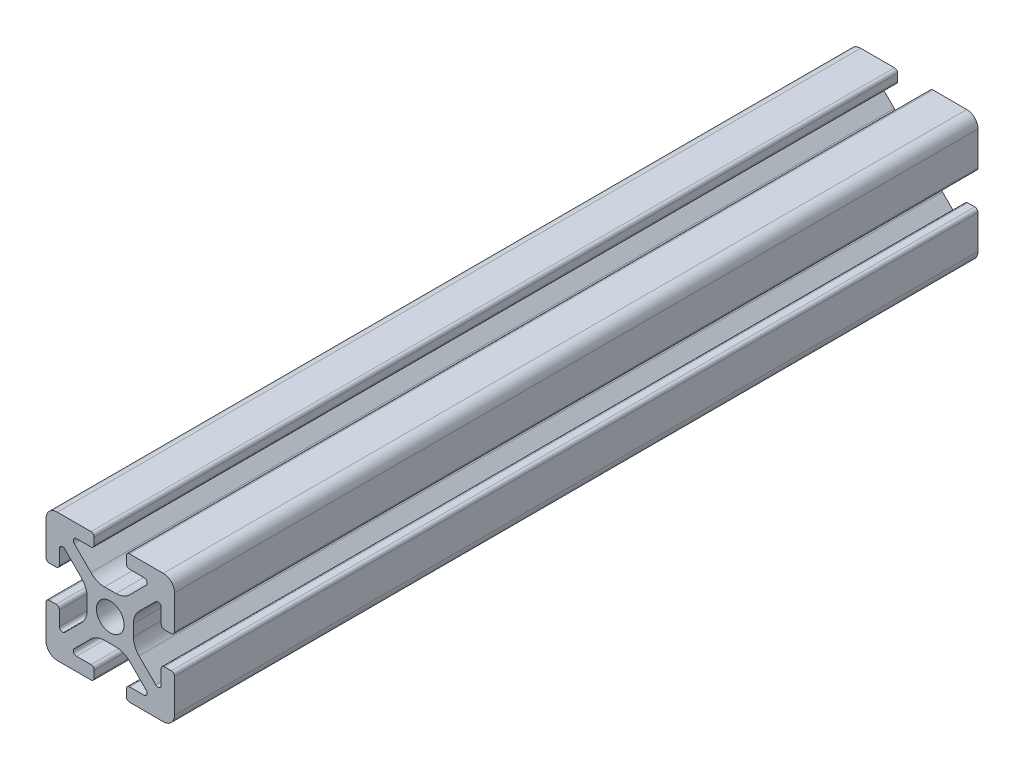
SolidWorks part; units mm, degrees
ref_plane "Front Plane" through (0, 0, 0) normal (0, 0, 1) x (1, 0, 0)
ref_plane "Top Plane" through (0, 0, 0) normal (0, 1, 0) x (1, 0, 0)
ref_plane "Right Plane" through (0, 0, 0) normal (1, 0, 0) x (0, 0, -1)
sketch "Sketch2" plane through (0, 0, 0) normal (0, 0, 1) x (1, 0, 0)
  line L0 (0, 10) -> (0, -10) construction
  line L1 (-10, 0) -> (10, 0) construction
  line L2 (2.5, -10) -> (10, -10)
  line L3 (10, -10) -> (10, -2.5)
  line L4 (2.5, -10) -> (2.5, -7.9246)
  line L5 (2.5, -7.9246) -> (6.4571, -7.9246)
  line L6 (6.4571, -7.9246) -> (2.1325, -3.6)
  line L7 (0, 0) -> (10, -10) construction
  line L8 (10, -2.5) -> (7.9246, -2.5)
  line L9 (7.9246, -2.5) -> (7.9246, -6.4571)
  line L10 (7.9246, -6.4571) -> (3.6, -2.1325)
  line L11 (5.7623, -4.2948) -> (4.2948, -5.7623) construction
  circle A0 centre (0, 0) radius 2.15
  arc A1 (5.25, -7.9246) -> (5.6036, -7.0711) centre (5.25, -7.4246) ccw construction
  point P8 (0, -3.6)
  point P16 (5.0286, -5.0286)
  dimension "Center Hole Diameter" = 4.3
  dimension "D3" = 0.5
  dimension "Rail Height" = 20
  dimension "Rail Width" = 20
  dimension "T-Slot Width" = 5
  dimension "Slot Depth" = 6.4
  dimension "Slot Inner Width" = 11.5
sketch "Sketch3" plane through (0, 0, 0) normal (1, 0, 0) x (0, 0, -1)
  line L0 (-457.2, -10) -> (457.2, -10) construction
  line L1 (-431.8, 0) -> (431.8, 0) construction
  line L2 (0, 10) -> (0, -10) construction
  line L3 (0, 10) -> (0, -10) construction
  point P6 (-431.8, 0)
  point P8 (431.8, 0)
  dimension "Length" = 914.4
  dimension "D1" = 25.4
sketch "Sketch4" plane through (0, 0, 0) normal (0, 0, 1) x (1, 0, 0)
  line L0 (3, -10) -> (8.25, -10)
  line L1 (2.5, -10) -> (10, -10) construction
  line L2 (2.5, -10) -> (2.5, -7.9246) construction
  line L3 (2.5, -7.9246) -> (6.4571, -7.9246) construction
  line L4 (2.5, -8.4246) -> (2.5, -9.5)
  line L5 (3, -7.9246) -> (5.25, -7.9246)
  line L6 (0, -3.6) -> (0.8898, -3.6)
  line L7 (6.4571, -7.9246) -> (2.1325, -3.6) construction
  line L8 (3.0112, -4.4787) -> (5.6036, -7.0711)
  line L9 (10, -10) -> (10, -2.5) construction
  line L10 (7.9246, -6.4571) -> (3.6, -2.1325) construction
  line L11 (7.9246, -2.5) -> (7.9246, -6.4571) construction
  line L12 (7.9246, -5.25) -> (7.9246, -3)
  line L13 (10, -2.5) -> (7.9246, -2.5) construction
  line L14 (8.4246, -2.5) -> (9.5, -2.5)
  line L15 (10, -3) -> (10, -8.25)
  line L16 (7.0711, -5.6036) -> (4.4787, -3.0112)
  line L17 (3.6, 0) -> (3.6, -0.8898)
  line L18 (-10, 0) -> (10, 0) construction
  line L19 (0, -3.6) -> (0, -2.15)
  line L20 (0, 10) -> (0, -10) construction
  line L21 (3.6, 0) -> (2.15, 0)
  arc A0 (2.5, -9.5) -> (3, -10) centre (3, -9.5) ccw
  arc A1 (5.25, -7.9246) -> (5.6036, -7.0711) centre (5.25, -7.4246) ccw construction
  arc A2 (2.5, -8.4246) -> (3, -7.9246) centre (3, -8.4246) cw
  arc A3 (5.25, -7.9246) -> (5.6036, -7.0711) centre (5.25, -7.4246) ccw
  arc A4 (0.8898, -3.6) -> (3.0112, -4.4787) centre (0.8898, -6.6) cw
  arc A5 (8.25, -10) -> (10, -8.25) centre (8.25, -8.25) ccw
  arc A6 (7.0711, -5.6036) -> (7.9246, -5.25) centre (7.4246, -5.25) ccw
  arc A7 (7.9246, -3) -> (8.4246, -2.5) centre (8.4246, -3) cw
  arc A8 (9.5, -2.5) -> (10, -3) centre (9.5, -3) cw
  arc A9 (4.4787, -3.0112) -> (3.6, -0.8898) centre (6.6, -0.8898) cw
  circle A10 centre (0, 0) radius 2.15 construction
  arc A11 (0, -2.15) -> (2.15, 0) centre (0, 0) ccw
  dimension "D1" = 1.75
  dimension "D2" = 3
extrude "Boss-Extrude1" add sketch "Sketch4" along normal mid plane 125
mirror "Mirror1" about plane through (0, 0, 0) normal (1, 0, 0) of bodies 134
mirror "Mirror2" about plane through (0, 0, 0) normal (0, 1, 0) of bodies 135
equation "\"D3@Sketch2\"=\"T-Slot Width@Sketch2\"*0.1"
equation "\"D1@Sketch4\"=\"D3@Sketch2\"*3.5"
equation "\"D2@Sketch4\"=\"D3@Sketch2\"*6"
equation "\"D1@Boss-Extrude1\"=\"Length@Sketch3\""
